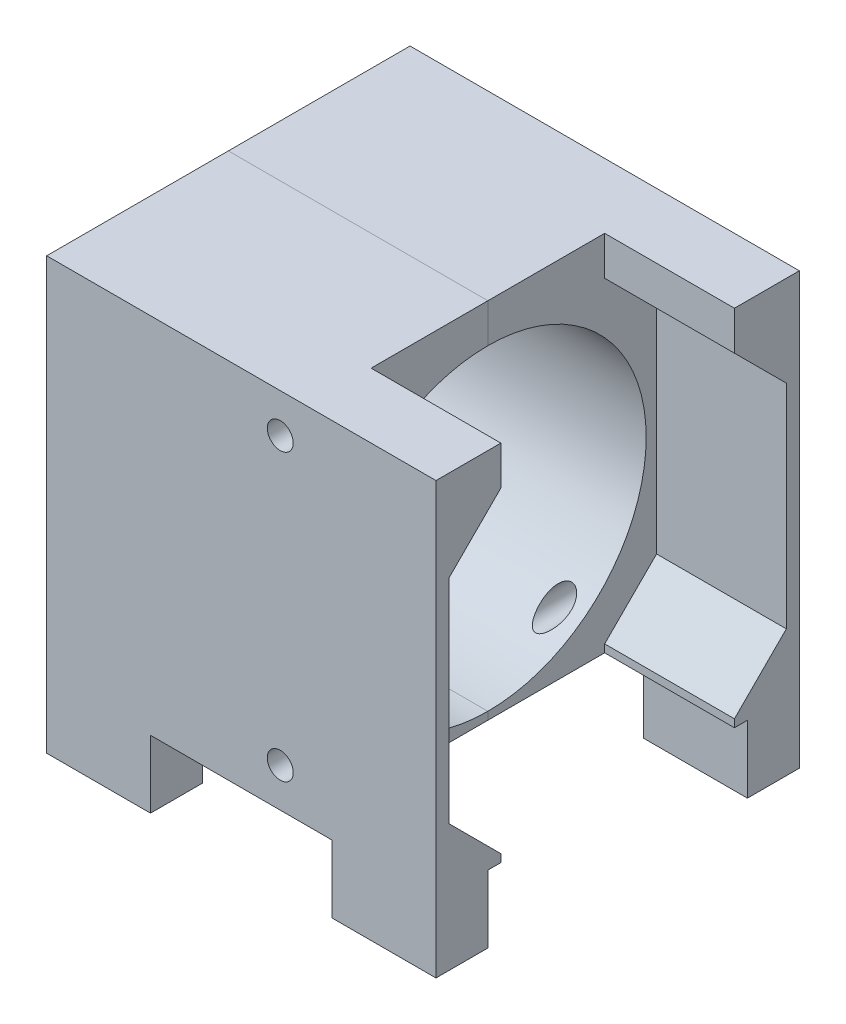
SolidWorks part; units mm, degrees
ref_plane "前视基准面" through (0, 0, 0) normal (0, 0, 1) x (1, 0, 0)
ref_plane "上视基准面" through (0, 0, 0) normal (0, 1, 0) x (1, 0, 0)
ref_plane "右视基准面" through (0, 0, 0) normal (1, 0, 0) x (0, 0, -1)
sketch "草图1" plane through (0, 0, 0) normal (1, 0, 0) x (0, 0, -1)
  line L1 (0, 12.2) -> (-14, 12.2)
  line L3 (0, -12.2) -> (-14, -12.2)
  line L4 (-14, 12.2) -> (-14, -12.2)
  arc A0 (0, 12.2) -> (0, -12.2) centre (0, 0) ccw
  dimension "D1" = 24.4
  dimension "D2" = 14
extrude "凸台-拉伸1" add sketch "草图1" along normal blind 20
sketch "草图2" plane through (20, 0, 0) normal (1, 0, 0) x (0, 0, -1)
  line L0 (-14, -12.2) -> (0, -12.2) construction
  line L1 (-14, 12.2) -> (-13, 12.2)
  line L2 (-14, 12.2) -> (-14, -12.2)
  line L3 (-14, -12.2) -> (-13, -12.2)
  line L4 (-13, 12.2) -> (-13, -12.2)
  dimension "D1" = 1
extrude "凸台-拉伸2" add sketch "草图2" along normal blind 10
sketch "草图6" plane through (0, -12.2, 0) normal (0, -1, 0) x (1, 0, 0)
  line L0 (0, 14) -> (0, 0)
  line L1 (0, 0) -> (20, 0)
  line L2 (20, 0) -> (20, 13)
  line L3 (20, 13) -> (30, 13)
  line L4 (30, 13) -> (30, 14)
  line L5 (30, 14) -> (0, 14)
extrude "凸台-拉伸4" add sketch "草图6" along normal blind 0.6
sketch "草图7" plane through (20, 0, 0) normal (1, 0, 0) x (0, 0, -1)
  line L0 (0, -12.2) -> (-9, -12.2)
  line L1 (-13, -12.8) -> (-13, 12.2) construction
  line L2 (-13, -8.2) -> (-9, -12.2)
  line L3 (-13, 8.2) -> (-9, 12.2)
  line L4 (0, 12.2) -> (-13, 12.2) construction
  line L5 (-9, 12.2) -> (-13, 12.2)
  line L6 (-13, 12.2) -> (-13, 8.2)
  line L7 (-13, -8.2) -> (-13, -12.8)
  line L8 (-13, -12.8) -> (0, -12.8)
  line L9 (0, -12.8) -> (0, -12.2)
  dimension "D1" = 45
  dimension "D3" = 4
  dimension "D4" = 45
extrude "凸台-拉伸5" add sketch "草图7" along normal up to surface (10 mm away) up to face at (30, -0.3, 13.5)
sketch "草图8" plane through (0, -12.8, 0) normal (0, -1, 0) x (1, 0, 0)
  line L0 (30, 0) -> (30, 14) construction
  line L1 (0, 14) -> (8, 14)
  line L2 (0, 14) -> (0, 10)
  line L3 (0, 10) -> (8, 10)
  line L4 (30, 14) -> (30, 10)
  line L5 (22, 10) -> (30, 10)
  line L7 (8, 14) -> (8, 10)
  line L9 (22, 14) -> (22, 10)
  line L10 (22, 14) -> (30, 14)
  dimension "D1" = 4
  dimension "D2" = 14
  dimension "D3" = 8
extrude "凸台-拉伸6" add sketch "草图8" along normal blind 5.2
sketch "草图9" plane through (0, 12.2, 0) normal (0, 1, 0) x (1, 0, 0)
  line L1 (0, 0) -> (20, 0)
  line L2 (0, 0) -> (0, -14)
  line L3 (0, -14) -> (30, -14)
  line L4 (30, -9) -> (30, -14)
  line L5 (20, -9) -> (30, -9)
  line L6 (20, -9) -> (20, 0)
extrude "凸台-拉伸7" add sketch "草图9" along normal blind 3
sketch "草图3" plane through (0, 0, 14) normal (0, 0, 1) x (1, 0, 0)
  line L1 (0, 15.2) -> (0, -18) construction
  line L2 (22, -12.8) -> (8, -12.8) construction
  circle A0 centre (18, 12.2) radius 1
  circle A1 centre (18, -9.8) radius 1
  dimension "D3" = 18
  dimension "D4" = 2
  dimension "D5" = 2
  dimension "D1" = 22
  dimension "D2" = 3
extrude "切除-拉伸1" cut sketch "草图3" against normal through all
sketch "草图10" plane through (0, -12.2, 0) normal (0, 1, 0) x (1, 0, 0)
  line L1 (20, -9) -> (30, -9)
  line L2 (20, -9) -> (20, 0)
  line L3 (20, 0) -> (30, 0)
  line L4 (30, -9) -> (30, 0)
extrude "切除-拉伸2" cut sketch "草图10" against normal blind 3
mirror "镜向4" about plane through (0, 15.2, 0) normal (0, 0, 1) of bodies 117
